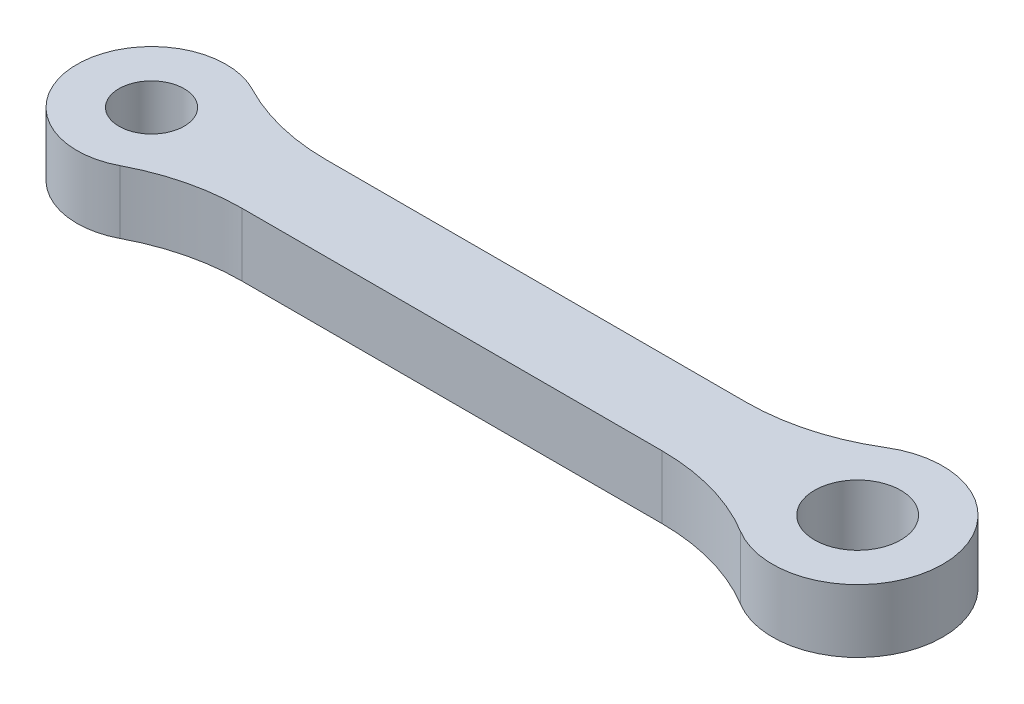
SolidWorks part; units mm, degrees
material "PLA 100% Infill"
ref_plane "Front Plane" through (0, 0, 0) normal (0, 0, 1) x (1, 0, 0)
ref_plane "Top Plane" through (0, 0, 0) normal (0, 1, 0) x (1, 0, 0)
ref_plane "Right Plane" through (0, 0, 0) normal (1, 0, 0) x (0, 0, -1)
sketch "Sketch1" plane through (0, 0, 0) normal (0, 1, 0) x (1, 0, 0)
  line L0 (0, 0) -> (-33.58, 0) construction
  line L1 (-30.03, 0) -> (-4.05, 0)
  line L2 (0, 2) -> (-33.58, 2)
  line L3 (0, -2) -> (-33.58, -2)
  circle A0 centre (0, 0) radius 2.05
  circle A1 centre (-33.58, 0) radius 1.55
  circle A2 centre (-33.58, 0) radius 3.55
  circle A3 centre (0, 0) radius 4.05
  dimension "D1" = 3.1
  dimension "D2" = 4.1
  dimension "D6" = 33.58
  dimension "D3" = 2
  dimension "D4" = 2
  dimension "D5" = 2
extrude "Boss-Extrude1" add sketch "Sketch1" along normal blind 3
fillet "Fillet1" radius 10 4 edges at (-30.647, 1.5, -2) (-3.5217, 1.5, -2) (-3.5217, 1.5, 2) (-30.647, 1.5, 2)
